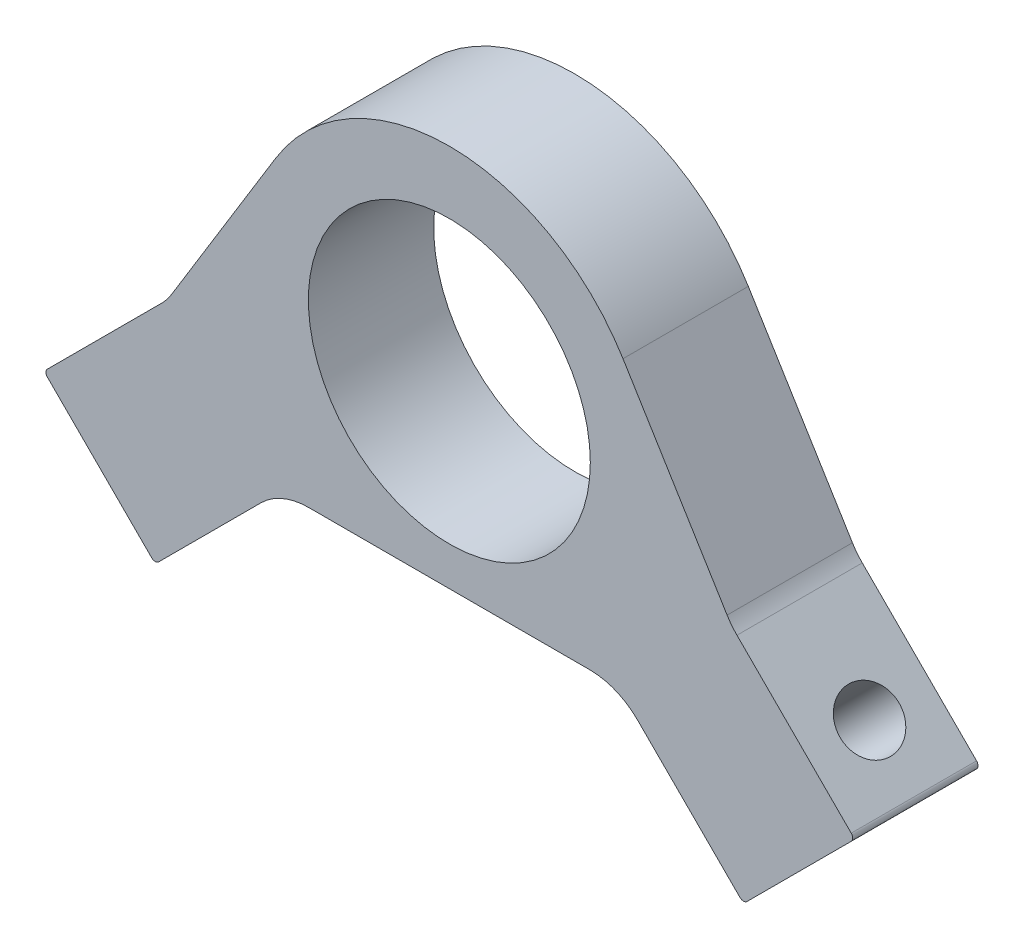
SolidWorks part; units mm, degrees
material "6061-T6 (SS)"
ref_plane "Front Plane" through (0, 0, 0) normal (0, 0, 1) x (1, 0, 0)
ref_plane "Top Plane" through (0, 0, 0) normal (0, 1, 0) x (1, 0, 0)
ref_plane "Right Plane" through (0, 0, 0) normal (1, 0, 0) x (0, 0, -1)
sketch "Sketch1" plane through (0, 0, 0) normal (0, 0, 1) x (1, 0, 0)
  line L0 (-48.9671, -44.583) -> (-17.0841, -12.7)
  line L1 (-17.0841, -12.7) -> (17.0841, -12.7)
  line L2 (17.0841, -12.7) -> (48.9671, -44.583)
  line L3 (0, -12.7) -> (0, 0) construction
  line L4 (60.2455, -33.3047) -> (48.9671, -44.583)
  line L5 (-60.2455, -33.3047) -> (-28.575, -1.6342)
  line L6 (-48.9671, -44.583) -> (-60.2455, -33.3047)
  line L7 (28.575, -1.6342) -> (60.2455, -33.3047)
  line L13 (-28.575, -1.6342) -> (-28.575, 33.0079)
  line L14 (-28.575, 33.0079) -> (28.575, 33.0079)
  line L15 (28.575, -1.6342) -> (28.575, 33.0079)
  circle A0 centre (0, 0) radius 14.2875 construction
  dimension "D1" = 28.575
  dimension "D4" = 12.7
  dimension "D5" = 15.95
  dimension "D6" = 19.05
  dimension "D2" = 135
  dimension "D3" = 57.15
  dimension "D8" = 15.95
extrude "Boss-Extrude1" add sketch "Sketch1" along normal mid plane 12.7
extrude "Cut-Extrude1" cut sketch "Sketch2" against normal through all
sketch "Sketch2" plane through (0, -92.9155, 6.35) normal (0, 0, 1) x (1, 0, 0)
  circle A0 centre (0, 98.425) radius 14.2875
hole_wizard "Ø6.0mm Clearance Dowel Hole1" positions "Sketch3" profile "Sketch4" hole size "Ø6.0" standard "ANSI Metric" end condition through all
sketch "Sketch3" plane through (-59.9281, -32.9874, 33.65) normal (-0.7071, 0.7071, 0) x (0, 0, 1)
  point P0 (-33.65, 33.4999)
  point P2 (0, 0)
sketch "Sketch4" plane through (-36.2401, -9.2994, 0) normal (0, 0, 1) x (-0.7071, -0.7071, 0)
  line L0 (0, 0) -> (0, 66.0843)
  line L1 (0, 66.0843) -> (3, 66.0843)
  line L2 (3, 66.0843) -> (3, 0)
  line L3 (3, 0) -> (0, 0)
  line L4 (0, -6.35) -> (0, 107.95) construction
  dimension "Thru Hole Dia." = 6
  dimension "Thru Hole Depth" = 66.0843
sketch "Sketch5" plane through (0, 0, 6.35) normal (0, 0, 1) x (1, 0, 0)
  line L0 (-41.0895, -14.1487) -> (-29.8111, -25.4271)
  line L1 (-28.575, -1.6342) -> (-60.2455, -33.3047) construction
  line L2 (-48.9671, -44.583) -> (-17.0841, -12.7) construction
  line L3 (-29.8111, -25.4271) -> (29.8111, -25.4271)
  line L4 (17.0841, -12.7) -> (48.9671, -44.583) construction
  line L5 (29.8111, -25.4271) -> (41.0895, -14.1487)
  line L6 (60.2455, -33.3047) -> (28.575, -1.6342) construction
  line L7 (41.0895, -14.1487) -> (91.8823, -14.1487)
  line L8 (91.8823, -14.1487) -> (91.8823, -80.2333)
  line L9 (91.8823, -80.2333) -> (-80.6756, -80.2333)
  line L10 (-80.6756, -80.2333) -> (-80.6756, -14.1487)
  line L11 (-80.6756, -14.1487) -> (-41.0895, -14.1487)
  line L12 (-24.9618, -20.5777) -> (-36.2401, -9.2994) construction
  dimension "D1" = 6.858
extrude "Cut-Extrude2" cut sketch "Sketch5" against normal through all
mirror "Mirror1" about plane through (0, 0, 0) normal (1, 0, 0) of "Ø6.0mm Clearance Dowel Hole1"
sketch "Sketch6" plane through (0, 0, 6.35) normal (0, 0, 1) x (1, 0, 0)
  line L0 (-28.575, -1.6342) -> (-17.5994, 16.2876)
  line L1 (-28.575, -1.6342) -> (-41.0895, -14.1487) construction
  line L2 (41.0895, -14.1487) -> (28.575, -1.6342) construction
  line L3 (-28.575, 33.0079) -> (-28.575, -1.6342) construction
  line L5 (17.5994, 16.2876) -> (28.575, -1.6342)
  line L6 (28.575, -1.6342) -> (28.575, 33.0079) construction
  line L8 (-28.575, -1.6342) -> (-28.575, 33.0079)
  line L9 (-28.575, 33.0079) -> (28.575, 33.0079)
  line L10 (28.575, 33.0079) -> (28.575, -1.6342)
  arc A0 (17.5994, 16.2876) -> (-17.5994, 16.2876) centre (0, 5.5095) ccw
  circle A1 centre (0, 5.5095) radius 14.2875 construction
  point P1 (-28.575, -2.1118)
  point P7 (-28.575, -1.6342)
  point P8 (0, 0)
  point P17 (0, 0)
  dimension "D1" = 6.35
extrude "Cut-Extrude3" cut sketch "Sketch6" against normal through all
fillet "Fillet1" radius 6.858 4 edges at (17.0841, -12.7, 0) (-17.0841, -12.7, 0) (28.575, -1.6342, 0) (-28.575, -1.6342, 0)
fillet "Fillet2" radius 0.508 4 edges at (41.0895, -14.1487, 0) (29.8111, -25.4271, 0) (-29.8111, -25.4271, 0) (-41.0895, -14.1487, 0)
